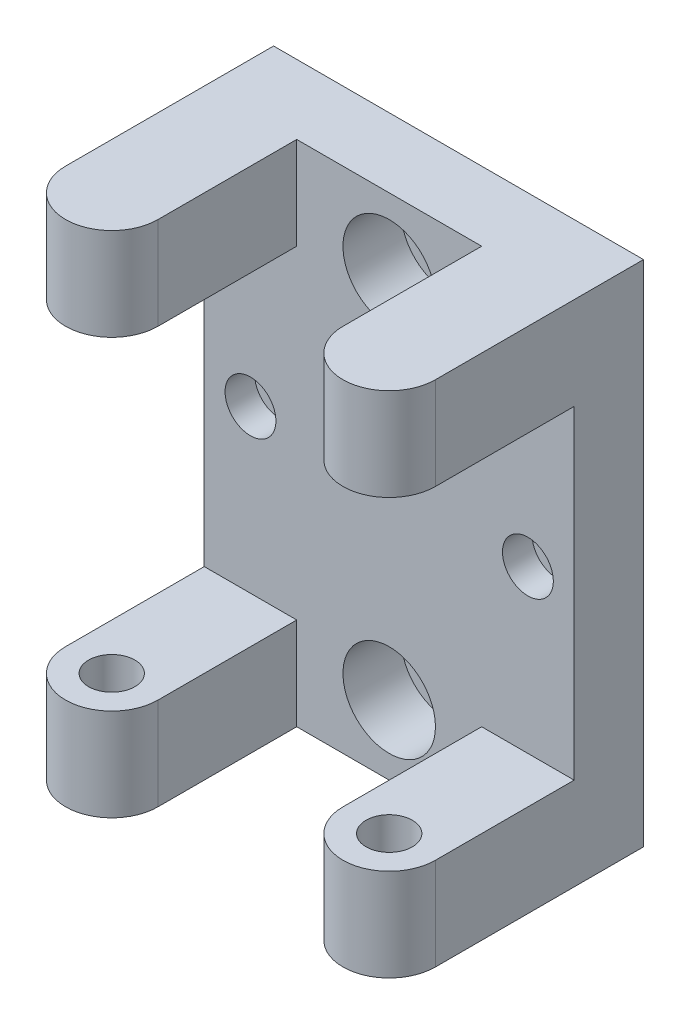
SolidWorks part; units mm, degrees
ref_plane "前视基准面" through (0, 0, 0) normal (0, 0, 1) x (1, 0, 0)
ref_plane "上视基准面" through (0, 0, 0) normal (0, 1, 0) x (1, 0, 0)
ref_plane "右视基准面" through (0, 0, 0) normal (1, 0, 0) x (0, 0, -1)
sketch "草图1" plane through (0, 0, 0) normal (0, 0, 1) x (1, 0, 0)
  line L1 (-40, 55) -> (40, 55)
  line L2 (-40, 55) -> (-40, -55)
  line L3 (-40, -55) -> (40, -55)
  line L4 (40, 55) -> (40, -55)
  line L5 (0, -55) -> (0, 55) construction
  line L6 (-40, 0) -> (40, 0) construction
  point P0 (0, 0)
  dimension "D1" = 110
  dimension "D2" = 80
extrude "凸台-拉伸1" add sketch "草图1" along normal blind 15
hole_wizard "M12 六角凹头螺钉的柱形沉头孔1" positions "草图2" profile "草图3" counterbore size "M12" standard "ISO" end condition through all
sketch "草图2" plane through (0, 0, 15) normal (0, 0, 1) x (1, 0, 0)
  point P0 (0, 40)
  point P2 (0, -40)
  dimension "D1" = 40
  dimension "D2" = 40
sketch "草图3" plane through (0, 40, 15) normal (1, 0, 0) x (0, -1, 0)
  line L0 (0, 0) -> (0, 15)
  line L1 (0, 15) -> (6.75, 15)
  line L3 (6.75, 15) -> (6.75, 12.6)
  line L4 (6.75, 12.6) -> (10, 12.6)
  line L5 (10, 12.6) -> (10, 0)
  line L7 (10, 0) -> (0, 0)
  line L11 (0, -6.35) -> (0, 107.95) construction
  dimension "通孔孔直径" = 13.5
  dimension "通孔孔深度" = 15
  dimension "柱形沉头孔直径" = 20
  dimension "柱形沉头孔深度" = 12.6
sketch "草图4" plane through (0, -55, 0) normal (0, -1, 0) x (1, 0, 0)
  line L0 (-40, 15) -> (-40, 45)
  line L1 (40, 15) -> (40, 45)
  line L2 (-20, 15) -> (-20, 45)
  line L3 (-40, 15) -> (40, 15) construction
  line L4 (20, 15) -> (20, 45)
  line L5 (-40, 15) -> (-20, 15)
  line L6 (20, 15) -> (40, 15)
  arc A0 (-40, 45) -> (-20, 45) centre (-30, 45) cw
  arc A1 (20, 45) -> (40, 45) centre (30, 45) cw
  dimension "D1" = 20
  dimension "D2" = 20
  dimension "D3" = 30
extrude "凸台-拉伸2" add sketch "草图4" against normal blind 20
ref_plane "基准面1" through (0, 0, 0) normal (0, -1, 0) x (-1, 0, 0)
mirror "镜向1" about plane through (0, 0, 0) normal (0, -1, 0) of "凸台-拉伸2"
sketch "草图5" plane through (0, -35, 0) normal (0, 1, 0) x (1, 0, 0)
  circle A0 centre (30, -45) radius 5
  circle A1 centre (-30, -45) radius 5
  dimension "D1" = 10
  dimension "D2" = 10
extrude "切除-拉伸1" cut sketch "草图5" against normal blind 10
mirror "镜向2" about plane through (0, 0, 0) normal (0, -1, 0) of "切除-拉伸1"
sketch "草图6" plane through (0, 35, 0) normal (0, -1, 0) x (1, 0, 0)
  point P0 (-30, 45)
  point P1 (30, 45)
hole_wizard "M6 六角凹头螺钉的柱形沉头孔1" positions "草图10" profile "草图11" counterbore size "M6" standard "ISO" end condition through all
sketch "草图10" plane through (0, 0, 15) normal (0, 0, 1) x (1, 0, 0)
  point P0 (-30, 0)
  point P2 (30, 0)
  dimension "D1" = 30
  dimension "D2" = 30
sketch "草图11" plane through (-30, 0, 15) normal (1, 0, 0) x (0, -1, 0)
  line L0 (0, 0) -> (0, 15)
  line L1 (0, 15) -> (3.3, 15)
  line L3 (3.3, 15) -> (3.3, 6.4)
  line L4 (3.3, 6.4) -> (5.5, 6.4)
  line L5 (5.5, 6.4) -> (5.5, 0)
  line L7 (5.5, 0) -> (0, 0)
  line L11 (0, -6.35) -> (0, 107.95) construction
  dimension "通孔孔直径" = 6.6
  dimension "通孔孔深度" = 15
  dimension "柱形沉头孔直径" = 11
  dimension "柱形沉头孔深度" = 6.4
sketch "草图13" plane through (0, 0, 0) normal (0, 0, -1) x (-1, 0, 0)
  line L0 (-30, 0) -> (30, 0)
